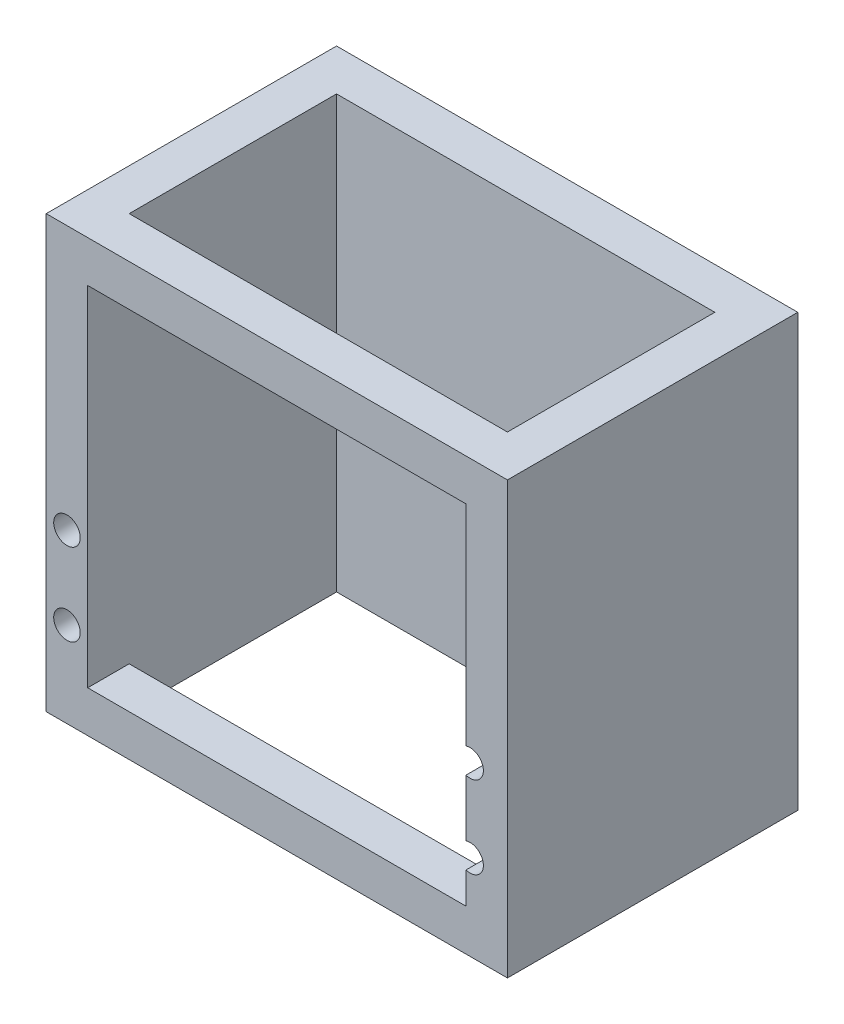
SolidWorks part; units mm, degrees
ref_plane "Front Plane" through (0, 0, 0) normal (0, 0, 1) x (1, 0, 0)
ref_plane "Top Plane" through (0, 0, 0) normal (0, 1, 0) x (1, 0, 0)
ref_plane "Right Plane" through (0, 0, 0) normal (1, 0, 0) x (0, 0, -1)
sketch "Sketch1" plane through (0, 0, 0) normal (0, 1, 0) x (1, 0, 0)
  line L1 (0, 0) -> (55.6, 0)
  line L2 (0, 0) -> (0, -35)
  line L3 (0, -35) -> (55.6, -35)
  line L4 (55.6, 0) -> (55.6, -35)
  line L5 (5, -5) -> (50.6, -5)
  line L6 (5, -5) -> (5, -30)
  line L7 (5, -30) -> (50.6, -30)
  line L8 (50.6, -5) -> (50.6, -30)
  dimension "D1" = 35
  dimension "D2" = 5
  dimension "D3" = 45.6
  dimension "D4" = 5
  dimension "D5" = 25
  dimension "D6" = 5
extrude "Boss-Extrude1" add sketch "Sketch1" along normal blind 52
sketch "Sketch2" plane through (0, 0, 35) normal (0, 0, 1) x (1, 0, 0)
  line L0 (0, 52) -> (0, 0) construction
  line L1 (5, 47) -> (50.6, 47)
  line L2 (5, 47) -> (5, 5)
  line L3 (5, 5) -> (50.6, 5)
  line L4 (50.6, 47) -> (50.6, 5)
  line L5 (55.6, 52) -> (55.6, 0) construction
  line L6 (0, 0) -> (55.6, 0) construction
  dimension "D1" = 5
  dimension "D2" = 5
  dimension "D3" = 5
  dimension "D4" = 42
extrude "Cut-Extrude1" cut sketch "Sketch2" against normal blind 5
sketch "Sketch3" plane through (0, 0, 35) normal (0, 0, 1) x (1, 0, 0)
  line L0 (6.8, 25.5) -> (46.8, 25.5)
  line L1 (6.8, 25.5) -> (6.8, 5)
  line L2 (6.8, 5) -> (46.8, 5)
  line L3 (46.8, 25.5) -> (46.8, 5)
  line L4 (6.8, 15.25) -> (46.8, 15.25) construction
  line L5 (26.8, 25.5) -> (26.8, 5) construction
  line L6 (5, 5) -> (50.6, 5) construction
  line L7 (0, 52) -> (0, 0) construction
  circle A0 centre (51.1, 20.2) radius 1.6
  circle A1 centre (51.1, 10.3) radius 1.6
  circle A2 centre (2.5, 10.3) radius 1.6
  circle A3 centre (2.5, 20.2) radius 1.6
  point P22 (0, 0)
  dimension "D3" = 3.2
  dimension "D4" = 3.2
  dimension "D5" = 3.2
  dimension "D6" = 3.2
  dimension "D1" = 40
  dimension "D2" = 20.5
  dimension "D7" = 9.9
  dimension "D8" = 9.9
  dimension "D9" = 48.6
  dimension "D10" = 48.6
  dimension "D11" = 24.3
  dimension "D12" = 24.3
  dimension "D13" = 24.3
  dimension "D14" = 5.3
  dimension "D15" = 0
  dimension "D16" = 2.5
extrude "Cut-Extrude2" cut sketch "Sketch3" against normal blind 5
